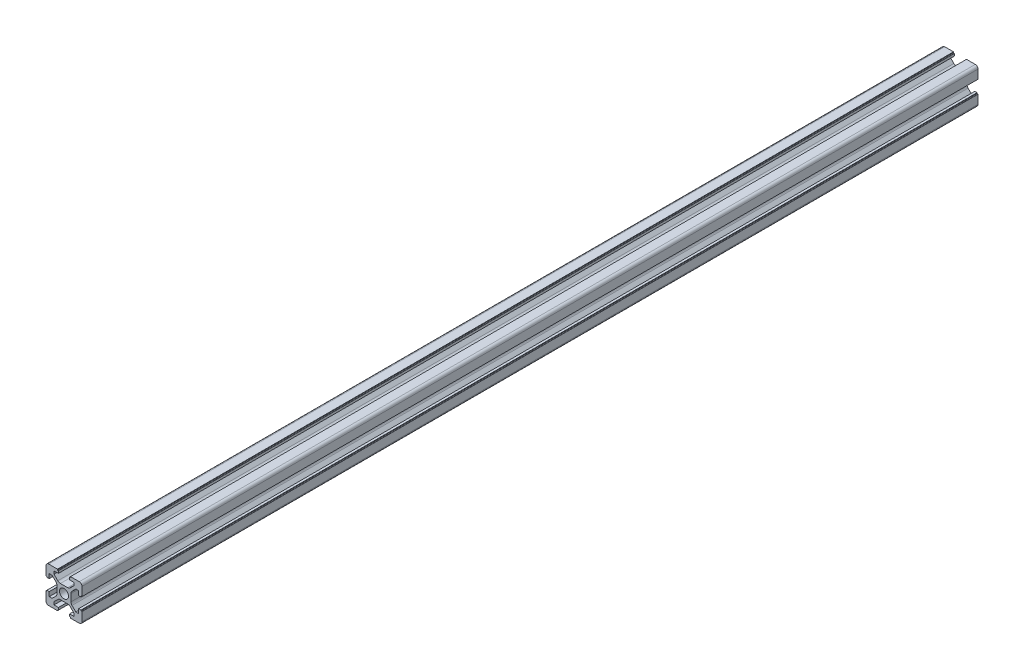
SolidWorks part; units mm, degrees
ref_plane "Спереди" through (0, 0, 0) normal (0, 0, 1) x (1, 0, 0)
ref_plane "Сверху" through (0, 0, 0) normal (0, 1, 0) x (1, 0, 0)
ref_plane "Справа" through (0, 0, 0) normal (1, 0, 0) x (0, 0, -1)
sketch "Sketch1" plane through (0, 0, 0) normal (0, 0, 1) x (1, 0, 0)
  line L0 (0, 10) -> (0, -10) construction
  line L1 (-10, -10) -> (10, -10) construction
  line L2 (-10, -10) -> (-10, 10) construction
  line L3 (-10, 10) -> (10, 10) construction
  line L4 (10, -10) -> (10, 10) construction
  line L5 (-10, -10) -> (10, 10) construction
  line L6 (-10, 10) -> (10, -10) construction
  line L7 (-10, 0) -> (10, 0) construction
  line L8 (0, 3.9) -> (-2.0109, 3.9)
  line L9 (-3.4251, 4.4858) -> (-5.5393, 6.6)
  line L10 (-5.5393, 6.6) -> (-5.5393, 8.2)
  line L11 (-5.5393, 8.2) -> (-3.1, 8.2)
  line L12 (-3.1, 8.2) -> (-3.1, 9.5)
  line L13 (-3.1, 9.5) -> (-3.4, 9.5)
  line L14 (-3.6, 9.7) -> (-3.6, 10)
  line L15 (-3.6, 10) -> (-8.5, 10)
  line L16 (-10, 3.6) -> (-10, 8.5)
  line L17 (-9.7, 3.6) -> (-10, 3.6)
  line L18 (-9.5, 3.1) -> (-9.5, 3.4)
  line L19 (-8.2, 3.1) -> (-9.5, 3.1)
  line L20 (-8.2, 5.5393) -> (-8.2, 3.1)
  line L21 (-6.6, 5.5393) -> (-8.2, 5.5393)
  line L22 (-4.4858, 3.4251) -> (-6.6, 5.5393)
  line L23 (-3.9, 0) -> (-3.9, 2.0109)
  line L24 (3.9, 0) -> (3.9, 2.0109)
  line L25 (4.4858, 3.4251) -> (6.6, 5.5393)
  line L26 (6.6, 5.5393) -> (8.2, 5.5393)
  line L27 (8.2, 5.5393) -> (8.2, 3.1)
  line L28 (8.2, 3.1) -> (9.5, 3.1)
  line L29 (9.5, 3.1) -> (9.5, 3.4)
  line L30 (9.7, 3.6) -> (10, 3.6)
  line L31 (10, 3.6) -> (10, 8.5)
  line L32 (3.6, 10) -> (8.5, 10)
  line L33 (3.6, 9.7) -> (3.6, 10)
  line L34 (3.1, 9.5) -> (3.4, 9.5)
  line L35 (3.1, 8.2) -> (3.1, 9.5)
  line L36 (5.5393, 8.2) -> (3.1, 8.2)
  line L37 (5.5393, 6.6) -> (5.5393, 8.2)
  line L38 (3.4251, 4.4858) -> (5.5393, 6.6)
  line L39 (0, 3.9) -> (2.0109, 3.9)
  line L40 (0, -3.9) -> (2.0109, -3.9)
  line L41 (3.4251, -4.4858) -> (5.5393, -6.6)
  line L42 (5.5393, -6.6) -> (5.5393, -8.2)
  line L43 (5.5393, -8.2) -> (3.1, -8.2)
  line L44 (3.1, -8.2) -> (3.1, -9.5)
  line L45 (3.1, -9.5) -> (3.4, -9.5)
  line L46 (3.6, -9.7) -> (3.6, -10)
  line L47 (3.6, -10) -> (8.5, -10)
  line L48 (10, -3.6) -> (10, -8.5)
  line L49 (9.7, -3.6) -> (10, -3.6)
  line L50 (9.5, -3.1) -> (9.5, -3.4)
  line L51 (8.2, -3.1) -> (9.5, -3.1)
  line L52 (8.2, -5.5393) -> (8.2, -3.1)
  line L53 (6.6, -5.5393) -> (8.2, -5.5393)
  line L54 (4.4858, -3.4251) -> (6.6, -5.5393)
  line L55 (3.9, 0) -> (3.9, -2.0109)
  line L56 (-3.9, 0) -> (-3.9, -2.0109)
  line L57 (-4.4858, -3.4251) -> (-6.6, -5.5393)
  line L58 (-6.6, -5.5393) -> (-8.2, -5.5393)
  line L59 (-8.2, -5.5393) -> (-8.2, -3.1)
  line L60 (-8.2, -3.1) -> (-9.5, -3.1)
  line L61 (-9.5, -3.1) -> (-9.5, -3.4)
  line L62 (-9.7, -3.6) -> (-10, -3.6)
  line L63 (-10, -3.6) -> (-10, -8.5)
  line L64 (-3.6, -10) -> (-8.5, -10)
  line L65 (-3.6, -9.7) -> (-3.6, -10)
  line L66 (-3.1, -9.5) -> (-3.4, -9.5)
  line L67 (-3.1, -8.2) -> (-3.1, -9.5)
  line L68 (-5.5393, -8.2) -> (-3.1, -8.2)
  line L69 (-5.5393, -6.6) -> (-5.5393, -8.2)
  line L70 (-3.4251, -4.4858) -> (-5.5393, -6.6)
  line L71 (0, -3.9) -> (-2.0109, -3.9)
  circle A0 centre (0, 0) radius 2.5
  arc A1 (-8.5, 10) -> (-10, 8.5) centre (-8.5, 8.5) ccw
  arc A2 (-2.0109, 3.9) -> (-3.4251, 4.4858) centre (-2.0109, 5.9) cw
  arc A3 (-3.4, 9.5) -> (-3.6, 9.7) centre (-3.4, 9.7) cw
  arc A4 (-9.5, 3.4) -> (-9.7, 3.6) centre (-9.7, 3.4) ccw
  arc A5 (-3.9, 2.0109) -> (-4.4858, 3.4251) centre (-5.9, 2.0109) ccw
  arc A6 (10, 8.5) -> (8.5, 10) centre (8.5, 8.5) ccw
  arc A7 (3.9, 2.0109) -> (4.4858, 3.4251) centre (5.9, 2.0109) cw
  arc A8 (9.5, 3.4) -> (9.7, 3.6) centre (9.7, 3.4) cw
  arc A9 (3.4, 9.5) -> (3.6, 9.7) centre (3.4, 9.7) ccw
  arc A10 (2.0109, 3.9) -> (3.4251, 4.4858) centre (2.0109, 5.9) ccw
  arc A11 (8.5, -10) -> (10, -8.5) centre (8.5, -8.5) ccw
  arc A12 (2.0109, -3.9) -> (3.4251, -4.4858) centre (2.0109, -5.9) cw
  arc A13 (3.4, -9.5) -> (3.6, -9.7) centre (3.4, -9.7) cw
  arc A14 (9.5, -3.4) -> (9.7, -3.6) centre (9.7, -3.4) ccw
  arc A15 (3.9, -2.0109) -> (4.4858, -3.4251) centre (5.9, -2.0109) ccw
  arc A16 (-10, -8.5) -> (-8.5, -10) centre (-8.5, -8.5) ccw
  arc A17 (-3.9, -2.0109) -> (-4.4858, -3.4251) centre (-5.9, -2.0109) cw
  arc A18 (-9.5, -3.4) -> (-9.7, -3.6) centre (-9.7, -3.4) cw
  arc A19 (-3.4, -9.5) -> (-3.6, -9.7) centre (-3.4, -9.7) ccw
  arc A20 (-2.0109, -3.9) -> (-3.4251, -4.4858) centre (-2.0109, -5.9) ccw
  point P0 (0, 0)
  point P42 (0, 0)
  point P70 (0, 0)
  point P98 (0, 0)
  point P126 (0, 0)
  dimension "D3" = 5
  dimension "D4" = 3
  dimension "D12" = 2
  dimension "D13" = 0.2
  dimension "D1" = 20
  dimension "D2" = 20
  dimension "D5" = 6.2
  dimension "D6" = 7.2
  dimension "D7" = 1.8
  dimension "D8" = 0.5
  dimension "D9" = 3.4
  dimension "D10" = 1.5
  dimension "D11" = 6.1
  dimension "D14" = 4
extrude "Extrude1" add sketch "Sketch1" along normal blind 498
